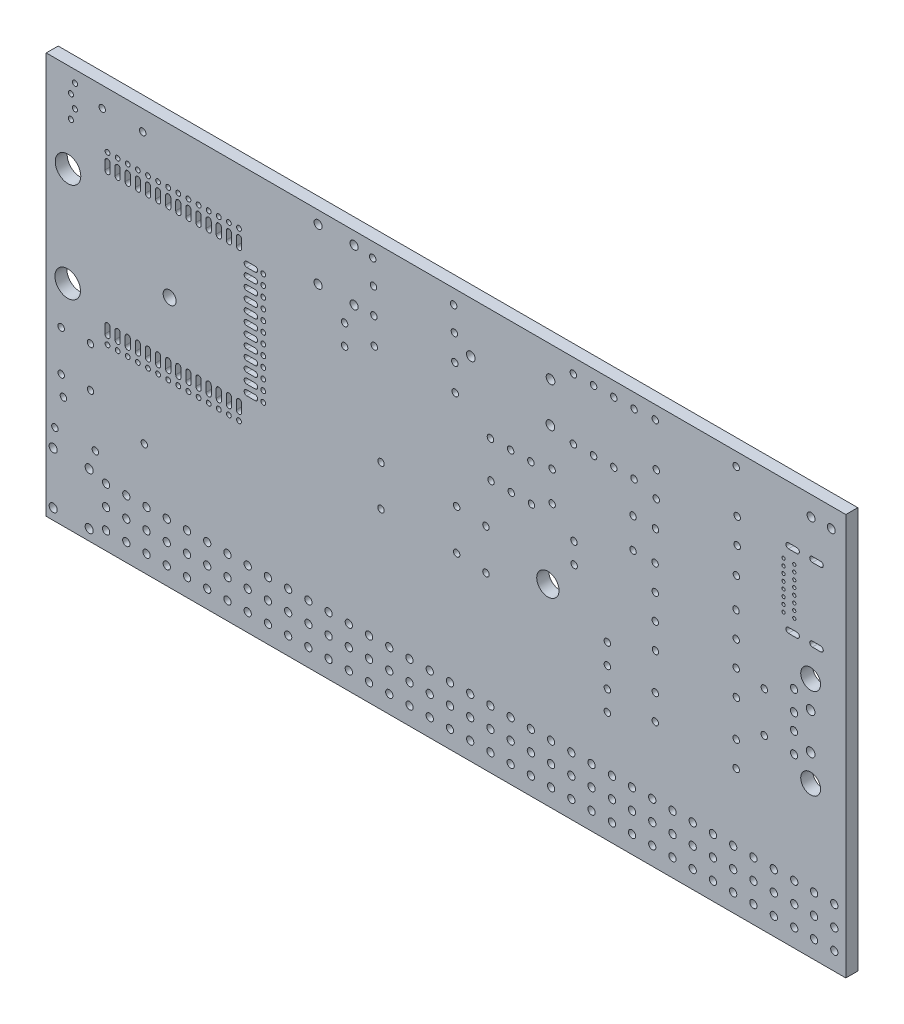
SolidWorks part; units mm, degrees
ref_plane "Front Plane" through (0, 0, 0) normal (0, 0, 1) x (1, 0, 0)
ref_plane "Top Plane" through (0, 0, 0) normal (0, 1, 0) x (1, 0, 0)
ref_plane "Right Plane" through (0, 0, 0) normal (1, 0, 0) x (0, 0, -1)
sketch "Sketch1" plane through (0, 0, 0) normal (0, 0, 1) x (1, 0, 0)
  line L0 (9.071, 43.739) -> (9.071, 43.039) construction
  line L1 (9.071, 43.039) -> (9.071, 41.339) construction
  line L2 (9.071, 42.714) -> (9.071, 41.664) construction
  line L3 (9.396, 42.714) -> (9.396, 41.664)
  line L8 (1.375, 50.708) -> (1.375, 0.308)
  line L9 (1.375, 0.308) -> (101.775, 0.308)
  line L10 (101.775, 0.308) -> (101.775, 50.708)
  line L11 (101.775, 50.708) -> (1.375, 50.708)
  line L12 (8.746, 42.714) -> (8.746, 41.664)
  line L13 (28.626, 40.304) -> (27.926, 40.304) construction
  line L14 (27.926, 40.304) -> (26.226, 40.304) construction
  line L15 (27.601, 40.304) -> (26.551, 40.304) construction
  line L16 (27.601, 39.979) -> (26.551, 39.979)
  line L17 (27.601, 40.629) -> (26.551, 40.629)
  line L18 (9.071, 22.809) -> (9.071, 23.509) construction
  line L19 (9.071, 23.509) -> (9.071, 25.209) construction
  line L20 (9.071, 23.834) -> (9.071, 24.884) construction
  line L21 (8.746, 23.834) -> (8.746, 24.884)
  line L22 (9.396, 23.834) -> (9.396, 24.884)
  line L23 (10.341, 23.834) -> (10.341, 24.884) construction
  line L24 (10.016, 23.834) -> (10.016, 24.884)
  line L25 (10.666, 23.834) -> (10.666, 24.884)
  line L26 (11.611, 23.834) -> (11.611, 24.884) construction
  line L27 (11.286, 23.834) -> (11.286, 24.884)
  line L28 (11.936, 23.834) -> (11.936, 24.884)
  line L29 (12.881, 23.834) -> (12.881, 24.884) construction
  line L30 (12.556, 23.834) -> (12.556, 24.884)
  line L31 (13.206, 23.834) -> (13.206, 24.884)
  line L32 (14.151, 23.834) -> (14.151, 24.884) construction
  line L33 (13.826, 23.834) -> (13.826, 24.884)
  line L34 (14.476, 23.834) -> (14.476, 24.884)
  line L35 (15.421, 23.834) -> (15.421, 24.884) construction
  line L36 (15.096, 23.834) -> (15.096, 24.884)
  line L37 (15.746, 23.834) -> (15.746, 24.884)
  line L38 (16.691, 23.834) -> (16.691, 24.884) construction
  line L39 (16.366, 23.834) -> (16.366, 24.884)
  line L40 (17.016, 23.834) -> (17.016, 24.884)
  line L41 (17.961, 23.834) -> (17.961, 24.884) construction
  line L42 (17.636, 23.834) -> (17.636, 24.884)
  line L43 (18.286, 23.834) -> (18.286, 24.884)
  line L44 (19.231, 23.834) -> (19.231, 24.884) construction
  line L45 (18.906, 23.834) -> (18.906, 24.884)
  line L46 (19.556, 23.834) -> (19.556, 24.884)
  line L47 (20.501, 23.834) -> (20.501, 24.884) construction
  line L48 (20.176, 23.834) -> (20.176, 24.884)
  line L49 (20.826, 23.834) -> (20.826, 24.884)
  line L50 (21.771, 23.834) -> (21.771, 24.884) construction
  line L51 (21.446, 23.834) -> (21.446, 24.884)
  line L52 (22.096, 23.834) -> (22.096, 24.884)
  line L53 (23.041, 23.834) -> (23.041, 24.884) construction
  line L54 (22.716, 23.834) -> (22.716, 24.884)
  line L55 (23.366, 23.834) -> (23.366, 24.884)
  line L56 (24.311, 23.834) -> (24.311, 24.884) construction
  line L57 (23.986, 23.834) -> (23.986, 24.884)
  line L58 (24.636, 23.834) -> (24.636, 24.884)
  line L59 (25.581, 23.834) -> (25.581, 24.884) construction
  line L60 (25.256, 23.834) -> (25.256, 24.884)
  line L61 (25.906, 23.834) -> (25.906, 24.884)
  line L62 (10.341, 42.714) -> (10.341, 41.664) construction
  line L63 (10.666, 42.714) -> (10.666, 41.664)
  line L64 (10.016, 42.714) -> (10.016, 41.664)
  line L65 (11.611, 42.714) -> (11.611, 41.664) construction
  line L66 (11.936, 42.714) -> (11.936, 41.664)
  line L67 (11.286, 42.714) -> (11.286, 41.664)
  line L68 (12.881, 42.714) -> (12.881, 41.664) construction
  line L69 (13.206, 42.714) -> (13.206, 41.664)
  line L70 (12.556, 42.714) -> (12.556, 41.664)
  line L71 (14.151, 42.714) -> (14.151, 41.664) construction
  line L72 (14.476, 42.714) -> (14.476, 41.664)
  line L73 (13.826, 42.714) -> (13.826, 41.664)
  line L74 (15.421, 42.714) -> (15.421, 41.664) construction
  line L75 (15.746, 42.714) -> (15.746, 41.664)
  line L76 (15.096, 42.714) -> (15.096, 41.664)
  line L77 (16.691, 42.714) -> (16.691, 41.664) construction
  line L78 (17.016, 42.714) -> (17.016, 41.664)
  line L79 (16.366, 42.714) -> (16.366, 41.664)
  line L80 (17.961, 42.714) -> (17.961, 41.664) construction
  line L81 (18.286, 42.714) -> (18.286, 41.664)
  line L82 (17.636, 42.714) -> (17.636, 41.664)
  line L83 (19.231, 42.714) -> (19.231, 41.664) construction
  line L84 (19.556, 42.714) -> (19.556, 41.664)
  line L85 (18.906, 42.714) -> (18.906, 41.664)
  line L86 (20.501, 42.714) -> (20.501, 41.664) construction
  line L87 (20.826, 42.714) -> (20.826, 41.664)
  line L88 (20.176, 42.714) -> (20.176, 41.664)
  line L89 (21.771, 42.714) -> (21.771, 41.664) construction
  line L90 (22.096, 42.714) -> (22.096, 41.664)
  line L91 (21.446, 42.714) -> (21.446, 41.664)
  line L92 (23.041, 42.714) -> (23.041, 41.664) construction
  line L93 (23.366, 42.714) -> (23.366, 41.664)
  line L94 (22.716, 42.714) -> (22.716, 41.664)
  line L95 (24.311, 42.714) -> (24.311, 41.664) construction
  line L96 (24.636, 42.714) -> (24.636, 41.664)
  line L97 (23.986, 42.714) -> (23.986, 41.664)
  line L98 (25.581, 42.714) -> (25.581, 41.664) construction
  line L99 (25.906, 42.714) -> (25.906, 41.664)
  line L100 (25.256, 42.714) -> (25.256, 41.664)
  line L101 (27.601, 39.034) -> (26.551, 39.034) construction
  line L102 (27.601, 38.709) -> (26.551, 38.709)
  line L103 (27.601, 39.359) -> (26.551, 39.359)
  line L104 (27.601, 37.764) -> (26.551, 37.764) construction
  line L105 (27.601, 37.439) -> (26.551, 37.439)
  line L106 (27.601, 38.089) -> (26.551, 38.089)
  line L107 (27.601, 36.494) -> (26.551, 36.494) construction
  line L108 (27.601, 36.169) -> (26.551, 36.169)
  line L109 (27.601, 36.819) -> (26.551, 36.819)
  line L110 (27.601, 35.224) -> (26.551, 35.224) construction
  line L111 (27.601, 34.899) -> (26.551, 34.899)
  line L112 (27.601, 35.549) -> (26.551, 35.549)
  line L113 (27.601, 33.954) -> (26.551, 33.954) construction
  line L114 (27.601, 33.629) -> (26.551, 33.629)
  line L115 (27.601, 34.279) -> (26.551, 34.279)
  line L116 (27.601, 32.684) -> (26.551, 32.684) construction
  line L117 (27.601, 32.359) -> (26.551, 32.359)
  line L118 (27.601, 33.009) -> (26.551, 33.009)
  line L119 (27.601, 31.414) -> (26.551, 31.414) construction
  line L120 (27.601, 31.089) -> (26.551, 31.089)
  line L121 (27.601, 31.739) -> (26.551, 31.739)
  line L122 (27.601, 30.144) -> (26.551, 30.144) construction
  line L123 (27.601, 29.819) -> (26.551, 29.819)
  line L124 (27.601, 30.469) -> (26.551, 30.469)
  line L125 (27.601, 28.874) -> (26.551, 28.874) construction
  line L126 (27.601, 28.549) -> (26.551, 28.549)
  line L127 (27.601, 29.199) -> (26.551, 29.199)
  line L227 (27.601, 27.604) -> (26.551, 27.604) construction
  line L458 (27.601, 27.279) -> (26.551, 27.279)
  line L640 (27.601, 27.929) -> (26.551, 27.929)
  line L641 (27.601, 26.334) -> (26.551, 26.334) construction
  line L642 (27.601, 26.009) -> (26.551, 26.009)
  line L643 (27.601, 26.659) -> (26.551, 26.659)
  line L649 (97.57, 34.519) -> (98.62, 34.519) construction
  line L650 (97.57, 34.844) -> (98.62, 34.844)
  line L651 (97.57, 34.194) -> (98.62, 34.194)
  line L652 (94.573, 34.519) -> (95.623, 34.519) construction
  line L653 (94.573, 34.844) -> (95.623, 34.844)
  line L654 (94.573, 34.194) -> (95.623, 34.194)
  line L655 (97.57, 43.719) -> (98.62, 43.719) construction
  line L656 (97.57, 44.044) -> (98.62, 44.044)
  line L657 (97.57, 43.394) -> (98.62, 43.394)
  line L658 (94.573, 43.713) -> (95.623, 43.713) construction
  line L659 (94.573, 44.038) -> (95.623, 44.038)
  line L660 (94.573, 43.388) -> (95.623, 43.388)
  circle A1 centre (4.1081, 39.459) radius 1.6049
  circle A3 centre (26.67, 2.54) radius 0.457
  circle A5 centre (29.21, 2.54) radius 0.457
  circle A7 centre (21.59, 7.62) radius 0.457
  circle A9 centre (19.05, 7.62) radius 0.457
  circle A11 centre (24.13, 7.62) radius 0.457
  circle A13 centre (13.691, 14.351) radius 0.406
  circle A15 centre (7.544, 10.516) radius 0.406
  circle A17 centre (13.97, 7.62) radius 0.457
  circle A19 centre (16.51, 7.62) radius 0.457
  circle A21 centre (8.89, 7.62) radius 0.457
  circle A23 centre (11.43, 7.62) radius 0.457
  circle A25 centre (6.934, 21.869) radius 0.406
  circle A27 centre (6.934, 16.789) radius 0.406
  circle A29 centre (3.251, 21.793) radius 0.406
  circle A31 centre (3.251, 16.713) radius 0.406
  circle A33 centre (3.531, 14.351) radius 0.406
  circle A35 centre (6.768, 8.179) radius 0.508
  circle A37 centre (2.464, 10.516) radius 0.406
  circle A39 centre (2.247, 8.179) radius 0.508
  circle A41 centre (24.13, 5.08) radius 0.457
  circle A43 centre (21.59, 5.08) radius 0.457
  circle A45 centre (26.67, 5.08) radius 0.457
  circle A47 centre (16.51, 5.08) radius 0.457
  circle A49 centre (19.05, 5.08) radius 0.457
  circle A51 centre (21.59, 2.54) radius 0.457
  circle A53 centre (24.13, 2.54) radius 0.457
  circle A55 centre (16.51, 2.54) radius 0.457
  circle A57 centre (19.05, 2.54) radius 0.457
  circle A59 centre (13.97, 5.08) radius 0.457
  circle A61 centre (13.97, 2.54) radius 0.457
  circle A63 centre (8.89, 5.08) radius 0.457
  circle A65 centre (11.43, 5.08) radius 0.457
  circle A67 centre (8.89, 2.54) radius 0.457
  circle A69 centre (11.43, 2.54) radius 0.457
  circle A71 centre (2.247, 1.676) radius 0.508
  circle A73 centre (6.768, 1.676) radius 0.508
  circle A75 centre (75.184, 48.895) radius 0.406
  circle A77 centre (77.978, 43.688) radius 0.406
  circle A79 centre (72.644, 48.895) radius 0.406
  circle A81 centre (75.184, 41.275) radius 0.406
  circle A83 centre (77.978, 40.513) radius 0.406
  circle A85 centre (77.876, 37.211) radius 0.406
  circle A87 centre (72.644, 41.275) radius 0.406
  circle A89 centre (75.057, 37.211) radius 0.406
  circle A91 centre (67.564, 48.895) radius 0.406
  circle A93 centre (70.104, 48.895) radius 0.406
  circle A95 centre (64.7, 46.874) radius 0.546
  circle A97 centre (64.68, 41.874) radius 0.546
  circle A99 centre (67.564, 41.275) radius 0.406
  circle A101 centre (70.104, 41.275) radius 0.406
  circle A103 centre (64.897, 37.211) radius 0.406
  circle A105 centre (57.15, 36.678) radius 0.406
  circle A107 centre (87.986, 33.452) radius 0.406
  circle A109 centre (77.826, 33.452) radius 0.406
  circle A111 centre (77.851, 30.277) radius 0.406
  circle A113 centre (75.057, 33.452) radius 0.406
  circle A115 centre (67.64, 30.734) radius 0.406
  circle A117 centre (88.011, 30.277) radius 0.406
  circle A119 centre (77.876, 23.952) radius 0.406
  circle A121 centre (67.666, 28.194) radius 0.406
  circle A123 centre (77.851, 27.127) radius 0.406
  circle A125 centre (64.897, 33.452) radius 0.406
  circle A127 centre (62.306, 32.106) radius 0.406
  circle A129 centre (59.69, 36.678) radius 0.406
  circle A131 centre (62.23, 36.678) radius 0.406
  circle A133 centre (59.766, 32.106) radius 0.406
  circle A135 centre (64.364, 24.435) radius 1.4
  circle A137 centre (57.226, 32.106) radius 0.406
  circle A139 centre (56.591, 26.848) radius 0.406
  circle A141 centre (97.358, 19.253) radius 1.245
  circle A143 centre (95.301, 7.645) radius 0.457
  circle A145 centre (97.79, 7.62) radius 0.457
  circle A147 centre (91.542, 21.565) radius 0.406
  circle A149 centre (95.275, 21.387) radius 0.45
  circle A151 centre (100.33, 7.62) radius 0.457
  circle A153 centre (95.301, 5.105) radius 0.457
  circle A155 centre (90.17, 7.62) radius 0.457
  circle A157 centre (92.735, 7.62) radius 0.457
  circle A159 centre (88.011, 19.38) radius 0.406
  circle A161 centre (88.011, 16.205) radius 0.406
  circle A163 centre (77.851, 19.38) radius 0.406
  circle A165 centre (77.851, 16.205) radius 0.406
  circle A167 centre (85.09, 7.62) radius 0.457
  circle A169 centre (87.63, 7.62) radius 0.457
  circle A171 centre (80.01, 7.62) radius 0.457
  circle A173 centre (82.55, 7.62) radius 0.457
  circle A175 centre (100.33, 5.08) radius 0.457
  circle A177 centre (97.79, 5.08) radius 0.457
  circle A179 centre (95.301, 2.565) radius 0.457
  circle A181 centre (90.17, 5.08) radius 0.457
  circle A183 centre (92.735, 5.08) radius 0.457
  circle A185 centre (97.79, 2.54) radius 0.457
  circle A187 centre (100.33, 2.54) radius 0.457
  circle A189 centre (90.17, 2.54) radius 0.457
  circle A191 centre (92.735, 2.54) radius 0.457
  circle A193 centre (85.09, 5.08) radius 0.457
  circle A195 centre (87.63, 5.08) radius 0.457
  circle A197 centre (80.01, 5.08) radius 0.457
  circle A199 centre (82.55, 5.08) radius 0.457
  circle A201 centre (85.09, 2.54) radius 0.457
  circle A203 centre (87.63, 2.54) radius 0.457
  circle A205 centre (80.01, 2.54) radius 0.457
  circle A207 centre (82.55, 2.54) radius 0.457
  circle A209 centre (71.832, 14.226) radius 0.406
  circle A211 centre (71.832, 16.766) radius 0.406
  circle A213 centre (77.47, 7.645) radius 0.457
  circle A215 centre (71.832, 21.846) radius 0.406
  circle A217 centre (71.832, 19.306) radius 0.406
  circle A219 centre (74.93, 7.62) radius 0.457
  circle A221 centre (77.47, 5.105) radius 0.457
  circle A223 centre (69.85, 7.62) radius 0.457
  circle A225 centre (72.415, 7.62) radius 0.457
  circle A227 centre (64.77, 7.62) radius 0.457
  circle A229 centre (67.31, 7.62) radius 0.457
  circle A231 centre (56.591, 21.768) radius 0.406
  circle A233 centre (62.23, 7.62) radius 0.457
  circle A235 centre (59.69, 7.62) radius 0.457
  circle A237 centre (69.85, 5.08) radius 0.457
  circle A239 centre (54.61, 7.62) radius 0.457
  circle A241 centre (57.15, 7.62) radius 0.457
  circle A243 centre (74.93, 5.08) radius 0.457
  circle A245 centre (72.415, 5.08) radius 0.457
  circle A247 centre (77.47, 2.565) radius 0.457
  circle A249 centre (64.77, 5.08) radius 0.457
  circle A251 centre (67.31, 5.08) radius 0.457
  circle A253 centre (72.415, 2.54) radius 0.457
  circle A255 centre (74.93, 2.54) radius 0.457
  circle A257 centre (67.31, 2.54) radius 0.457
  circle A259 centre (69.85, 2.54) radius 0.457
  circle A261 centre (59.69, 5.08) radius 0.457
  circle A263 centre (62.23, 5.08) radius 0.457
  circle A265 centre (57.15, 5.08) radius 0.457
  circle A267 centre (54.61, 2.54) radius 0.457
  circle A269 centre (62.23, 2.54) radius 0.457
  circle A271 centre (64.77, 2.54) radius 0.457
  circle A273 centre (57.15, 2.54) radius 0.457
  circle A275 centre (59.69, 2.54) radius 0.457
  circle A277 centre (52.629, 45.898) radius 0.406
  circle A279 centre (52.527, 48.895) radius 0.406
  circle A281 centre (54.69, 44.374) radius 0.546
  circle A283 centre (42.367, 48.895) radius 0.406
  circle A285 centre (42.469, 45.898) radius 0.406
  circle A287 centre (52.68, 42.697) radius 0.406
  circle A289 centre (52.73, 39.421) radius 0.406
  circle A291 centre (42.52, 42.697) radius 0.406
  circle A293 centre (42.57, 39.421) radius 0.406
  circle A295 centre (40.03, 49.124) radius 0.508
  circle A297 centre (35.509, 49.124) radius 0.508
  circle A299 centre (25.581, 43.739) radius 0.3
  circle A301 centre (23.041, 43.739) radius 0.3
  circle A303 centre (24.311, 43.739) radius 0.3
  circle A305 centre (40.03, 42.621) radius 0.508
  circle A307 centre (38.837, 40.081) radius 0.406
  circle A309 centre (35.509, 42.621) radius 0.508
  circle A311 centre (28.626, 40.304) radius 0.3
  circle A313 centre (28.626, 37.764) radius 0.3
  circle A315 centre (28.626, 39.034) radius 0.3
  circle A317 centre (38.837, 37.541) radius 0.406
  circle A319 centre (28.626, 35.224) radius 0.3
  circle A321 centre (28.626, 33.954) radius 0.3
  circle A323 centre (43.409, 27.203) radius 0.406
  circle A325 centre (52.908, 27.153) radius 0.406
  circle A327 centre (28.626, 32.684) radius 0.3
  circle A329 centre (43.409, 22.123) radius 0.406
  circle A331 centre (28.626, 30.144) radius 0.3
  circle A333 centre (28.626, 28.874) radius 0.3
  circle A335 centre (28.626, 36.494) radius 0.3
  circle A337 centre (28.626, 31.414) radius 0.3
  circle A339 centre (28.626, 27.604) radius 0.3
  circle A341 centre (28.626, 26.334) radius 0.3
  circle A343 centre (24.311, 22.809) radius 0.3
  circle A345 centre (25.581, 22.809) radius 0.3
  circle A347 centre (20.501, 43.739) radius 0.3
  circle A349 centre (19.231, 43.739) radius 0.3
  circle A351 centre (21.771, 43.739) radius 0.3
  circle A353 centre (13.487, 48.184) radius 0.406
  circle A355 centre (17.961, 43.739) radius 0.3
  circle A357 centre (15.421, 43.739) radius 0.3
  circle A359 centre (16.691, 43.739) radius 0.3
  circle A361 centre (12.881, 43.739) radius 0.3
  circle A363 centre (14.151, 43.739) radius 0.3
  circle A365 centre (4.98, 49.219) radius 0.325
  circle A367 centre (8.407, 48.184) radius 0.406
  circle A369 centre (4.472, 47.822) radius 0.325
  circle A371 centre (4.98, 46.425) radius 0.325
  circle A373 centre (10.341, 43.739) radius 0.3
  circle A375 centre (11.611, 43.739) radius 0.3
  circle A377 centre (4.472, 45.028) radius 0.325
  circle A379 centre (9.071, 43.739) radius 0.3
  circle A381 centre (21.771, 22.809) radius 0.3
  circle A383 centre (20.501, 22.809) radius 0.3
  circle A385 centre (23.041, 22.809) radius 0.3
  circle A387 centre (16.871, 31.862) radius 0.82
  circle A389 centre (19.231, 22.809) radius 0.3
  circle A391 centre (16.691, 22.809) radius 0.3
  circle A393 centre (17.961, 22.809) radius 0.3
  circle A395 centre (14.151, 22.809) radius 0.3
  circle A397 centre (15.421, 22.809) radius 0.3
  circle A399 centre (95.301, 36.182) radius 0.203
  circle A401 centre (97.358, 27.229) radius 0.546
  circle A403 centre (97.358, 22.644) radius 0.546
  circle A405 centre (95.275, 25.959) radius 0.45
  circle A407 centre (95.275, 23.927) radius 0.45
  circle A409 centre (93.955, 37.859) radius 0.203
  circle A411 centre (93.955, 37.02) radius 0.203
  circle A413 centre (88.036, 37.211) radius 0.406
  circle A415 centre (93.955, 36.182) radius 0.203
  circle A419 centre (91.542, 26.645) radius 0.406
  circle A421 centre (88.011, 27.127) radius 0.406
  circle A423 centre (88.036, 23.952) radius 0.406
  circle A425 centre (77.851, 49.047) radius 0.406
  circle A427 centre (95.301, 38.697) radius 0.203
  circle A429 centre (95.301, 37.859) radius 0.203
  circle A431 centre (95.301, 40.373) radius 0.203
  circle A433 centre (95.301, 39.535) radius 0.203
  circle A437 centre (93.955, 42.05) radius 0.203
  circle A439 centre (93.955, 41.212) radius 0.203
  circle A441 centre (88.011, 49.047) radius 0.406
  circle A443 centre (88.138, 43.688) radius 0.406
  circle A445 centre (93.955, 40.373) radius 0.203
  circle A447 centre (93.955, 39.535) radius 0.203
  circle A449 centre (88.138, 40.513) radius 0.406
  circle A451 centre (93.955, 38.697) radius 0.203
  circle A455 centre (97.358, 30.632) radius 1.245
  circle A457 centre (95.275, 28.499) radius 0.45
  circle A459 centre (95.301, 37.02) radius 0.203
  circle A461 centre (34.29, 2.54) radius 0.457
  circle A463 centre (31.75, 2.54) radius 0.457
  circle A465 centre (34.29, 5.08) radius 0.457
  circle A467 centre (31.75, 5.08) radius 0.457
  circle A469 centre (36.83, 2.54) radius 0.457
  circle A471 centre (36.83, 5.08) radius 0.457
  circle A473 centre (41.91, 2.54) radius 0.457
  circle A475 centre (39.37, 2.54) radius 0.457
  circle A477 centre (46.99, 2.54) radius 0.457
  circle A479 centre (44.45, 2.54) radius 0.457
  circle A481 centre (41.91, 5.08) radius 0.457
  circle A483 centre (39.37, 5.08) radius 0.457
  circle A485 centre (49.53, 2.54) radius 0.457
  circle A487 centre (52.07, 5.08) radius 0.457
  circle A489 centre (52.07, 2.54) radius 0.457
  circle A491 centre (29.21, 5.08) radius 0.457
  circle A493 centre (26.67, 7.62) radius 0.457
  circle A495 centre (31.75, 7.62) radius 0.457
  circle A497 centre (29.21, 7.62) radius 0.457
  circle A499 centre (36.83, 7.62) radius 0.457
  circle A501 centre (34.29, 7.62) radius 0.457
  circle A503 centre (41.91, 7.62) radius 0.457
  circle A505 centre (39.37, 7.62) radius 0.457
  circle A507 centre (46.99, 5.08) radius 0.457
  circle A509 centre (44.45, 5.08) radius 0.457
  circle A511 centre (54.61, 5.08) radius 0.457
  circle A513 centre (49.53, 5.08) radius 0.457
  circle A515 centre (46.99, 7.62) radius 0.457
  circle A517 centre (95.301, 41.212) radius 0.203
  circle A519 centre (95.301, 42.05) radius 0.203
  circle A521 centre (9.071, 22.809) radius 0.3
  circle A523 centre (10.341, 22.809) radius 0.3
  circle A525 centre (52.908, 22.073) radius 0.406
  circle A527 centre (52.07, 7.62) radius 0.457
  circle A529 centre (49.53, 7.62) radius 0.457
  circle A531 centre (44.45, 7.62) radius 0.457
  circle A533 centre (11.611, 22.809) radius 0.3
  circle A535 centre (12.881, 22.809) radius 0.3
  circle A539 centre (97.409, 48.26) radius 0.5
  circle A541 centre (99.949, 48.26) radius 0.5
  circle A542 centre (4.067, 26.975) radius 1.6049
  arc A543 (9.396, 42.714) -> (8.746, 42.714) centre (9.071, 42.714) ccw
  arc A544 (8.746, 41.664) -> (9.396, 41.664) centre (9.071, 41.664) ccw
  arc A545 (27.601, 39.979) -> (27.601, 40.629) centre (27.601, 40.304) ccw
  arc A546 (26.551, 40.629) -> (26.551, 39.979) centre (26.551, 40.304) ccw
  arc A547 (8.746, 23.834) -> (9.396, 23.834) centre (9.071, 23.834) ccw
  arc A548 (9.396, 24.884) -> (8.746, 24.884) centre (9.071, 24.884) ccw
  arc A549 (10.016, 23.834) -> (10.666, 23.834) centre (10.341, 23.834) ccw
  arc A550 (10.666, 24.884) -> (10.016, 24.884) centre (10.341, 24.884) ccw
  arc A551 (11.286, 23.834) -> (11.936, 23.834) centre (11.611, 23.834) ccw
  arc A552 (11.936, 24.884) -> (11.286, 24.884) centre (11.611, 24.884) ccw
  arc A553 (12.556, 23.834) -> (13.206, 23.834) centre (12.881, 23.834) ccw
  arc A554 (13.206, 24.884) -> (12.556, 24.884) centre (12.881, 24.884) ccw
  arc A555 (13.826, 23.834) -> (14.476, 23.834) centre (14.151, 23.834) ccw
  arc A556 (14.476, 24.884) -> (13.826, 24.884) centre (14.151, 24.884) ccw
  arc A557 (15.096, 23.834) -> (15.746, 23.834) centre (15.421, 23.834) ccw
  arc A558 (15.746, 24.884) -> (15.096, 24.884) centre (15.421, 24.884) ccw
  arc A559 (16.366, 23.834) -> (17.016, 23.834) centre (16.691, 23.834) ccw
  arc A560 (17.016, 24.884) -> (16.366, 24.884) centre (16.691, 24.884) ccw
  arc A561 (17.636, 23.834) -> (18.286, 23.834) centre (17.961, 23.834) ccw
  arc A562 (18.286, 24.884) -> (17.636, 24.884) centre (17.961, 24.884) ccw
  arc A563 (18.906, 23.834) -> (19.556, 23.834) centre (19.231, 23.834) ccw
  arc A564 (19.556, 24.884) -> (18.906, 24.884) centre (19.231, 24.884) ccw
  arc A565 (20.176, 23.834) -> (20.826, 23.834) centre (20.501, 23.834) ccw
  arc A566 (20.826, 24.884) -> (20.176, 24.884) centre (20.501, 24.884) ccw
  arc A567 (21.446, 23.834) -> (22.096, 23.834) centre (21.771, 23.834) ccw
  arc A568 (22.096, 24.884) -> (21.446, 24.884) centre (21.771, 24.884) ccw
  arc A569 (22.716, 23.834) -> (23.366, 23.834) centre (23.041, 23.834) ccw
  arc A570 (23.366, 24.884) -> (22.716, 24.884) centre (23.041, 24.884) ccw
  arc A571 (23.986, 23.834) -> (24.636, 23.834) centre (24.311, 23.834) ccw
  arc A572 (24.636, 24.884) -> (23.986, 24.884) centre (24.311, 24.884) ccw
  arc A573 (25.256, 23.834) -> (25.906, 23.834) centre (25.581, 23.834) ccw
  arc A574 (25.906, 24.884) -> (25.256, 24.884) centre (25.581, 24.884) ccw
  arc A575 (10.666, 42.714) -> (10.016, 42.714) centre (10.341, 42.714) ccw
  arc A576 (10.016, 41.664) -> (10.666, 41.664) centre (10.341, 41.664) ccw
  arc A577 (11.936, 42.714) -> (11.286, 42.714) centre (11.611, 42.714) ccw
  arc A578 (11.286, 41.664) -> (11.936, 41.664) centre (11.611, 41.664) ccw
  arc A579 (13.206, 42.714) -> (12.556, 42.714) centre (12.881, 42.714) ccw
  arc A580 (12.556, 41.664) -> (13.206, 41.664) centre (12.881, 41.664) ccw
  arc A581 (14.476, 42.714) -> (13.826, 42.714) centre (14.151, 42.714) ccw
  arc A582 (13.826, 41.664) -> (14.476, 41.664) centre (14.151, 41.664) ccw
  arc A583 (15.746, 42.714) -> (15.096, 42.714) centre (15.421, 42.714) ccw
  arc A584 (15.096, 41.664) -> (15.746, 41.664) centre (15.421, 41.664) ccw
  arc A585 (17.016, 42.714) -> (16.366, 42.714) centre (16.691, 42.714) ccw
  arc A586 (16.366, 41.664) -> (17.016, 41.664) centre (16.691, 41.664) ccw
  arc A587 (18.286, 42.714) -> (17.636, 42.714) centre (17.961, 42.714) ccw
  arc A588 (17.636, 41.664) -> (18.286, 41.664) centre (17.961, 41.664) ccw
  arc A589 (19.556, 42.714) -> (18.906, 42.714) centre (19.231, 42.714) ccw
  arc A590 (18.906, 41.664) -> (19.556, 41.664) centre (19.231, 41.664) ccw
  arc A591 (20.826, 42.714) -> (20.176, 42.714) centre (20.501, 42.714) ccw
  arc A592 (20.176, 41.664) -> (20.826, 41.664) centre (20.501, 41.664) ccw
  arc A593 (22.096, 42.714) -> (21.446, 42.714) centre (21.771, 42.714) ccw
  arc A594 (21.446, 41.664) -> (22.096, 41.664) centre (21.771, 41.664) ccw
  arc A595 (23.366, 42.714) -> (22.716, 42.714) centre (23.041, 42.714) ccw
  arc A596 (22.716, 41.664) -> (23.366, 41.664) centre (23.041, 41.664) ccw
  arc A597 (24.636, 42.714) -> (23.986, 42.714) centre (24.311, 42.714) ccw
  arc A598 (23.986, 41.664) -> (24.636, 41.664) centre (24.311, 41.664) ccw
  arc A599 (25.906, 42.714) -> (25.256, 42.714) centre (25.581, 42.714) ccw
  arc A600 (25.256, 41.664) -> (25.906, 41.664) centre (25.581, 41.664) ccw
  arc A601 (27.601, 38.709) -> (27.601, 39.359) centre (27.601, 39.034) ccw
  arc A602 (26.551, 39.359) -> (26.551, 38.709) centre (26.551, 39.034) ccw
  arc A603 (27.601, 37.439) -> (27.601, 38.089) centre (27.601, 37.764) ccw
  arc A604 (26.551, 38.089) -> (26.551, 37.439) centre (26.551, 37.764) ccw
  arc A605 (27.601, 36.169) -> (27.601, 36.819) centre (27.601, 36.494) ccw
  arc A606 (26.551, 36.819) -> (26.551, 36.169) centre (26.551, 36.494) ccw
  arc A607 (27.601, 34.899) -> (27.601, 35.549) centre (27.601, 35.224) ccw
  arc A608 (26.551, 35.549) -> (26.551, 34.899) centre (26.551, 35.224) ccw
  arc A609 (27.601, 33.629) -> (27.601, 34.279) centre (27.601, 33.954) ccw
  arc A610 (26.551, 34.279) -> (26.551, 33.629) centre (26.551, 33.954) ccw
  arc A611 (27.601, 32.359) -> (27.601, 33.009) centre (27.601, 32.684) ccw
  arc A612 (26.551, 33.009) -> (26.551, 32.359) centre (26.551, 32.684) ccw
  arc A614 (27.601, 31.089) -> (27.601, 31.739) centre (27.601, 31.414) ccw
  arc A616 (26.551, 31.739) -> (26.551, 31.089) centre (26.551, 31.414) ccw
  arc A618 (27.601, 29.819) -> (27.601, 30.469) centre (27.601, 30.144) ccw
  arc A619 (26.551, 30.469) -> (26.551, 29.819) centre (26.551, 30.144) ccw
  arc A620 (27.601, 28.549) -> (27.601, 29.199) centre (27.601, 28.874) ccw
  arc A621 (26.551, 29.199) -> (26.551, 28.549) centre (26.551, 28.874) ccw
  arc A623 (27.601, 27.279) -> (27.601, 27.929) centre (27.601, 27.604) ccw
  arc A625 (26.551, 27.929) -> (26.551, 27.279) centre (26.551, 27.604) ccw
  arc A627 (27.601, 26.009) -> (27.601, 26.659) centre (27.601, 26.334) ccw
  arc A628 (26.551, 26.659) -> (26.551, 26.009) centre (26.551, 26.334) ccw
  arc A632 (97.57, 34.844) -> (97.57, 34.194) centre (97.57, 34.519) ccw
  arc A633 (98.62, 34.194) -> (98.62, 34.844) centre (98.62, 34.519) ccw
  arc A634 (94.573, 34.844) -> (94.573, 34.194) centre (94.573, 34.519) ccw
  arc A635 (95.623, 34.194) -> (95.623, 34.844) centre (95.623, 34.519) ccw
  arc A636 (97.57, 44.044) -> (97.57, 43.394) centre (97.57, 43.719) ccw
  arc A637 (98.62, 43.394) -> (98.62, 44.044) centre (98.62, 43.719) ccw
  arc A638 (94.573, 44.038) -> (94.573, 43.388) centre (94.573, 43.713) ccw
  arc A639 (95.623, 43.388) -> (95.623, 44.038) centre (95.623, 43.713) ccw
  point P112 (95.098, 34.519)
  point P125 (98.095, 43.719)
  point P135 (9.071, 42.714)
  point P143 (9.071, 42.189)
  point P145 (98.095, 34.519)
  point P163 (95.098, 43.713)
  point P167 (9.071, 42.189)
  point P231 (27.601, 40.304)
  point P239 (27.076, 40.304)
  point P263 (27.076, 40.304)
  point P327 (9.071, 23.834)
  point P335 (9.071, 24.359)
  point P359 (9.071, 24.359)
  point P841 (10.341, 24.359)
  point P861 (11.611, 24.359)
  point P875 (12.881, 24.359)
  point P889 (14.151, 24.359)
  point P905 (15.421, 24.359)
  point P935 (16.691, 24.359)
  point P965 (17.961, 24.359)
  point P1003 (19.231, 24.359)
  point P1086 (20.501, 24.359)
  point P1102 (21.771, 24.359)
  point P1118 (23.041, 24.359)
  point P1139 (24.311, 24.359)
  point P1147 (25.581, 24.359)
  point P1153 (10.341, 42.189)
  point P1160 (11.611, 42.189)
  point P1167 (12.881, 42.189)
  point P1174 (14.151, 42.189)
  point P1181 (15.421, 42.189)
  point P1188 (16.691, 42.189)
  point P1195 (17.961, 42.189)
  point P1202 (19.231, 42.189)
  point P1209 (20.501, 42.189)
  point P1216 (21.771, 42.189)
  point P1223 (23.041, 42.189)
  point P1230 (24.311, 42.189)
  point P1237 (25.581, 42.189)
  point P1244 (27.076, 39.034)
  point P1260 (27.076, 37.764)
  point P1293 (27.076, 36.494)
  point P1321 (27.076, 35.224)
  point P1349 (27.076, 33.954)
  point P1377 (27.076, 32.684)
  point P1405 (27.076, 31.414)
  point P1427 (27.076, 30.144)
  point P1434 (27.076, 28.874)
  point P1441 (27.076, 27.604)
  point P1448 (27.076, 26.334)
extrude "Boss-Extrude1" add sketch "Sketch1" along normal blind 1.5
sketch "cmp"
sketch "sol"
